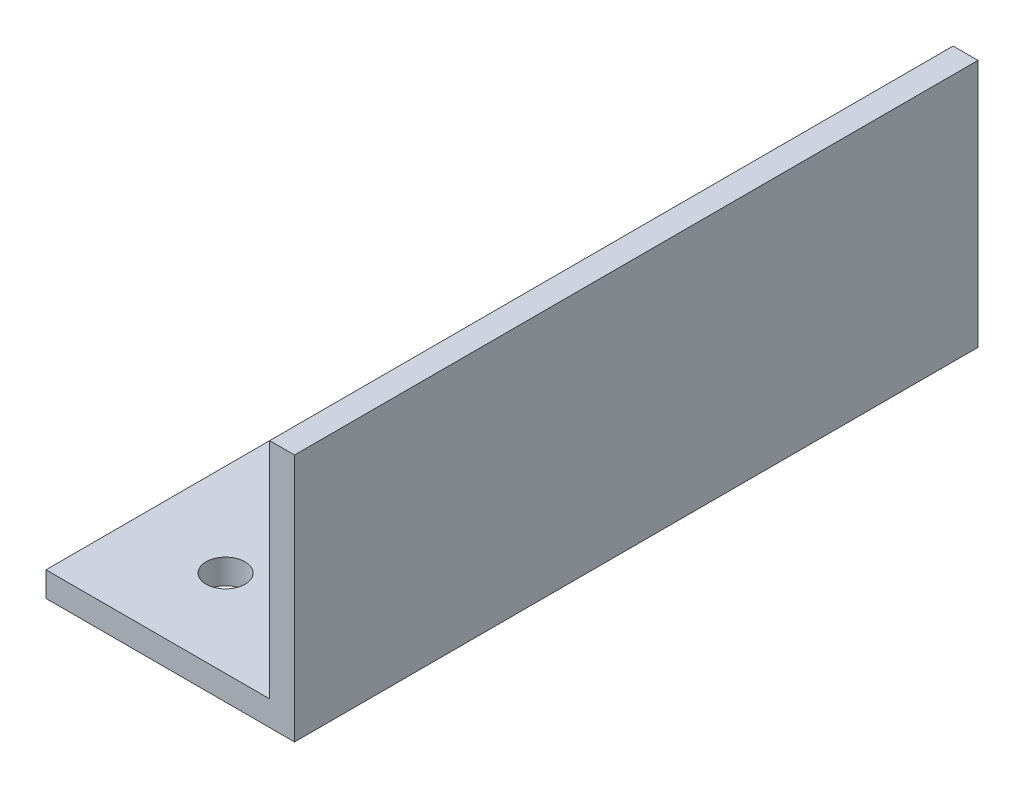
SolidWorks part; units mm, degrees
ref_plane "Спереди" through (0, 0, 0) normal (0, 0, 1) x (1, 0, 0)
ref_plane "Сверху" through (0, 0, 0) normal (0, 1, 0) x (1, 0, 0)
ref_plane "Справа" through (0, 0, 0) normal (1, 0, 0) x (0, 0, -1)
sketch "Эскиз1" plane through (0, 0, 0) normal (0, 0, 1) x (1, 0, 0)
  line L1 (0, 0) -> (2, 0)
  line L2 (0, 0) -> (0, 20)
  line L3 (0, 20) -> (2, 20)
  line L4 (2, 0) -> (2, 20)
  line L5 (0, 0) -> (-18, 0)
  line L6 (0, 0) -> (0, 2)
  line L7 (0, 2) -> (-18, 2)
  line L8 (-18, 0) -> (-18, 2)
  dimension "D1" = 20
  dimension "D2" = 20
  dimension "D3" = 2
  dimension "D4" = 2
extrude "Бобышка-Вытянуть1" add sketch "Эскиз1" along normal blind 55 contours L8 L5 L2 L7 | L1 L4 L3 L2
sketch "Эскиз2" plane through (0, 0, 0) normal (0, -1, 0) x (1, 0, 0)
  circle A0 centre (-10.5502, 7) radius 1.5662
  circle A1 centre (-10.5502, 48) radius 1.5662
extrude "Вырез-Вытянуть1" cut sketch "Эскиз2" against normal blind 10
